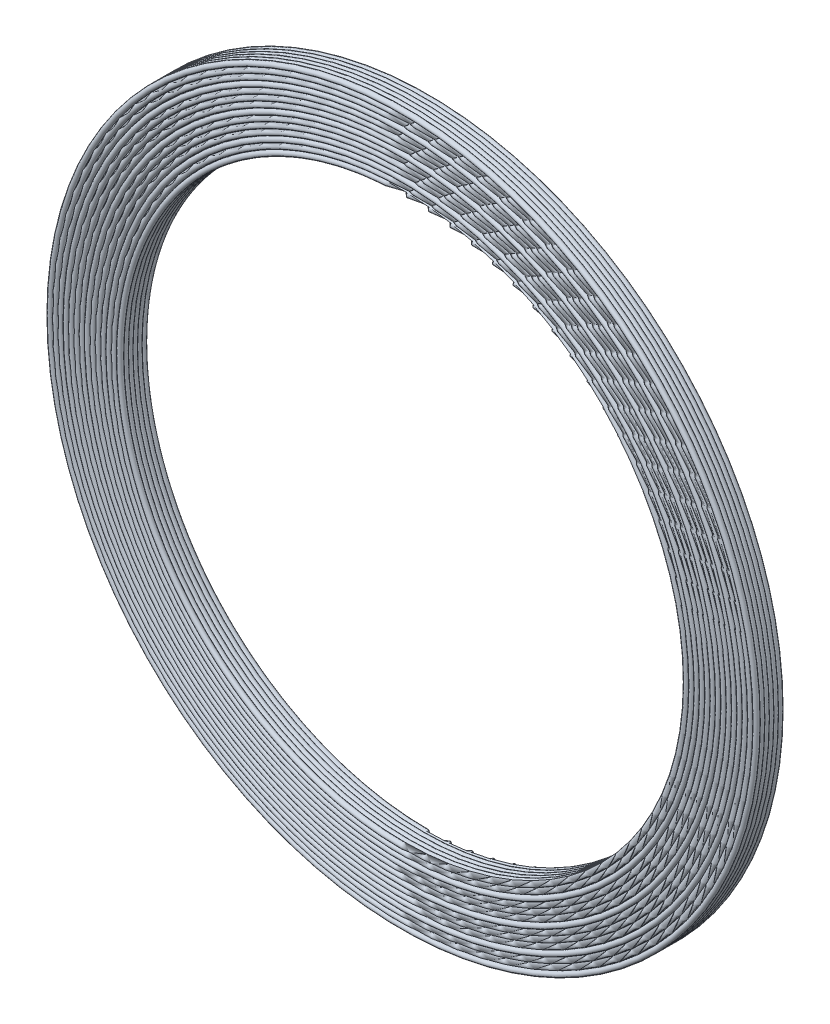
SolidWorks part; units mm, degrees
material "Медь"
ref_plane "Front" through (0, 0, 0) normal (0, 0, 1) x (1, 0, 0)
ref_plane "Top" through (0, 0, 0) normal (0, 1, 0) x (1, 0, 0)
ref_plane "Right" through (0, 0, 0) normal (1, 0, 0) x (0, 0, -1)
sketch "Эскиз1" plane through (0, 0, 0) normal (0, 1, 0) x (1, 0, 0)
  line L0 (-15, 0) -> (-19, 0) construction
  line L1 (-19, 0) -> (-19, -1.5) construction
  line L2 (-19, -1.5) -> (-15, -1.5) construction
  line L3 (-15, -1.5) -> (-15, 0) construction
  line L5 (0, -2.2807) -> (0, 0) construction
  line L6 (-18.8571, -1.3571) -> (-15.1429, -1.3571) construction
  line L7 (-15.0676, -1.2357) -> (-15.0676, -0.75) construction
  line L8 (-19, -0.75) -> (-15, -0.75) construction
  line L9 (-18.9324, -1.2357) -> (-18.9324, -0.75) construction
  arc A0 (-18.7143, -1.3571) -> (-18.9324, -1.2357) centre (-18.8571, -1.3571) cw
  arc A1 (-18.7143, -1.3571) -> (-18.4286, -1.3571) centre (-18.5714, -1.3571) ccw
  arc A2 (-18.4286, -1.3571) -> (-18.1429, -1.3571) centre (-18.2857, -1.3571) ccw
  arc A3 (-18.1429, -1.3571) -> (-17.8571, -1.3571) centre (-18, -1.3571) ccw
  arc A4 (-17.8571, -1.3571) -> (-17.5714, -1.3571) centre (-17.7143, -1.3571) ccw
  arc A5 (-17.5714, -1.3571) -> (-17.2857, -1.3571) centre (-17.4286, -1.3571) ccw
  arc A6 (-17.2857, -1.3571) -> (-17, -1.3571) centre (-17.1429, -1.3571) ccw
  arc A7 (-17, -1.3571) -> (-16.7143, -1.3571) centre (-16.8571, -1.3571) ccw
  arc A8 (-16.7143, -1.3571) -> (-16.4286, -1.3571) centre (-16.5714, -1.3571) ccw
  arc A9 (-16.4286, -1.3571) -> (-16.1429, -1.3571) centre (-16.2857, -1.3571) ccw
  arc A10 (-16.1429, -1.3571) -> (-15.8571, -1.3571) centre (-16, -1.3571) ccw
  arc A11 (-15.8571, -1.3571) -> (-15.5714, -1.3571) centre (-15.7143, -1.3571) ccw
  arc A12 (-15.5714, -1.3571) -> (-15.2857, -1.3571) centre (-15.4286, -1.3571) ccw
  arc A13 (-15.2857, -1.3571) -> (-15.0676, -1.2357) centre (-15.1429, -1.3571) ccw
  arc A14 (-18.9324, -1.2357) -> (-18.9324, -0.9929) centre (-18.8571, -1.1143) cw
  arc A15 (-18.9324, -0.9929) -> (-18.9324, -0.75) centre (-18.8571, -0.8714) cw
  arc A16 (-15.0676, -1.2357) -> (-15.0676, -0.9929) centre (-15.1429, -1.1143) ccw
  arc A17 (-15.0676, -0.9929) -> (-15.0676, -0.75) centre (-15.1429, -0.8714) ccw
  arc A18 (-15.0676, -0.5071) -> (-15.0676, -0.75) centre (-15.1429, -0.6286) cw
  arc A19 (-15.0676, -0.2643) -> (-15.0676, -0.5071) centre (-15.1429, -0.3857) cw
  arc A20 (-18.9324, -0.5071) -> (-18.9324, -0.75) centre (-18.8571, -0.6286) ccw
  arc A21 (-18.9324, -0.2643) -> (-18.9324, -0.5071) centre (-18.8571, -0.3857) ccw
  arc A22 (-15.2857, -0.1429) -> (-15.0676, -0.2643) centre (-15.1429, -0.1429) cw
  arc A23 (-15.5714, -0.1429) -> (-15.2857, -0.1429) centre (-15.4286, -0.1429) cw
  arc A24 (-15.8571, -0.1429) -> (-15.5714, -0.1429) centre (-15.7143, -0.1429) cw
  arc A25 (-16.1429, -0.1429) -> (-15.8571, -0.1429) centre (-16, -0.1429) cw
  arc A26 (-16.4286, -0.1429) -> (-16.1429, -0.1429) centre (-16.2857, -0.1429) cw
  arc A27 (-16.7143, -0.1429) -> (-16.4286, -0.1429) centre (-16.5714, -0.1429) cw
  arc A28 (-17, -0.1429) -> (-16.7143, -0.1429) centre (-16.8571, -0.1429) cw
  arc A29 (-17.2857, -0.1429) -> (-17, -0.1429) centre (-17.1429, -0.1429) cw
  arc A30 (-17.5714, -0.1429) -> (-17.2857, -0.1429) centre (-17.4286, -0.1429) cw
  arc A31 (-17.8571, -0.1429) -> (-17.5714, -0.1429) centre (-17.7143, -0.1429) cw
  arc A32 (-18.1429, -0.1429) -> (-17.8571, -0.1429) centre (-18, -0.1429) cw
  arc A33 (-18.4286, -0.1429) -> (-18.1429, -0.1429) centre (-18.2857, -0.1429) cw
  arc A34 (-18.7143, -0.1429) -> (-18.4286, -0.1429) centre (-18.5714, -0.1429) cw
  arc A35 (-18.7143, -0.1429) -> (-18.9324, -0.2643) centre (-18.8571, -0.1429) ccw
  point P6 (0, -6.2866)
  point P13 (-15, -0.75)
  point P44 (-15.0676, -0.75)
  point P45 (-18.9324, -0.75)
  point P49 (0, -2.2807)
  dimension "D1" = 1.5
  dimension "D2" = 15
  dimension "D3" = 19
revolve "Повернуть1" add sketch "Эскиз1" angle 360 about L5
